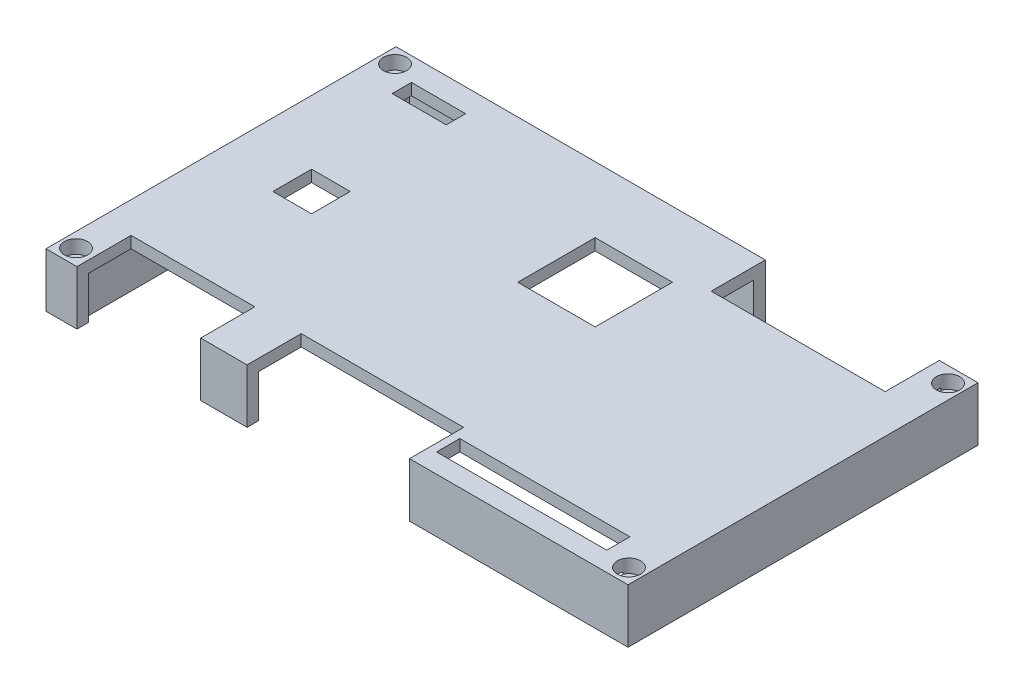
SolidWorks part; units mm, degrees
material "ABS"
ref_plane "Front Plane" through (0, 0, 0) normal (0, 0, 1) x (1, 0, 0)
ref_plane "Top Plane" through (0, 0, 0) normal (0, 1, 0) x (1, 0, 0)
ref_plane "Right Plane" through (0, 0, 0) normal (1, 0, 0) x (0, 0, -1)
other "Configuration Table"
sketch "Sketch1" plane through (0, 0, 0) normal (0, 1, 0) x (1, 0, 0)
  line L1 (75.25, -45.25) -> (-75.25, -45.25)
  line L2 (75.25, -45.25) -> (75.25, 45.25)
  line L3 (75.25, 45.25) -> (-75.25, 45.25)
  line L4 (-75.25, -45.25) -> (-75.25, 45.25)
  line L5 (75.25, -45.25) -> (-75.25, 45.25) construction
  line L6 (75.25, 45.25) -> (-75.25, -45.25) construction
  point P0 (0, 0)
  dimension "D1" = 90.5
  dimension "D2" = 150.5
extrude "Boss-Extrude1" add sketch "Sketch1" along normal blind 3
sketch "Sketch2" plane through (0, 0, 0) normal (0, -1, 0) x (-1, 0, 0)
  line L0 (75.25, -45.25) -> (-75.25, -45.25) construction
  line L1 (-68.75, 42.25) -> (68.75, 42.25)
  line L2 (-68.75, 42.25) -> (-68.75, -42.25)
  line L3 (-68.75, -42.25) -> (68.75, -42.25)
  line L4 (68.75, 42.25) -> (68.75, -42.25)
  line L5 (-68.75, 42.25) -> (68.75, -42.25) construction
  line L6 (-68.75, -42.25) -> (68.75, 42.25) construction
  line L7 (75.25, 45.25) -> (75.25, -45.25) construction
  line L8 (75.25, 45.25) -> (75.25, -45.25)
  line L9 (75.25, -45.25) -> (-75.25, -45.25)
  line L10 (-75.25, -45.25) -> (-75.25, 45.25)
  line L11 (-75.25, 45.25) -> (75.25, 45.25)
  point P0 (0, 0)
  dimension "D1" = 3
  dimension "D2" = 6.5
extrude "Boss-Extrude2" add sketch "Sketch2" along normal blind 11
sketch "Sketch3" plane through (0, 3, 0) normal (0, 1, 0) x (1, 0, 0)
  line L1 (71.5, -41.25) -> (-71.5, -41.25) construction
  line L2 (71.5, -41.25) -> (71.5, 41.25) construction
  line L3 (71.5, 41.25) -> (-71.5, 41.25) construction
  line L4 (-71.5, -41.25) -> (-71.5, 41.25) construction
  line L5 (71.5, -41.25) -> (-71.5, 41.25) construction
  line L6 (71.5, 41.25) -> (-71.5, -41.25) construction
  circle A0 centre (-71.5, 41.25) radius 1.5
  circle A1 centre (-71.5, -41.25) radius 1.5
  circle A2 centre (71.5, -41.25) radius 1.5
  circle A3 centre (71.5, 41.25) radius 1.5
  point P0 (0, 0)
  dimension "D3" = 3
  dimension "D4" = 3
  dimension "D5" = 3
  dimension "D6" = 3
  dimension "D1" = 82.5
  dimension "D2" = 143
extrude "Cut-Extrude1" cut sketch "Sketch3" against normal blind 31
sketch "Sketch4" plane through (0, 3, 0) normal (0, 1, 0) x (1, 0, 0)
  circle A0 centre (-71.5, 41.25) radius 3
  circle A1 centre (-71.5, -41.25) radius 3
  circle A2 centre (71.5, -41.25) radius 3
  circle A3 centre (71.5, 41.25) radius 3
  dimension "D1" = 6
  dimension "D2" = 6
  dimension "D3" = 6
  dimension "D4" = 6
extrude "Cut-Extrude2" cut sketch "Sketch4" against normal blind 3.5
sketch "Sketch5" plane through (0, 3, 0) normal (0, 1, 0) x (1, 0, 0)
  line L0 (-75.25, -45.25) -> (75.25, -45.25) construction
  line L1 (-67.25, -45.25) -> (-35.25, -45.25)
  line L2 (-67.25, -45.25) -> (-67.25, -31.25)
  line L3 (-67.25, -31.25) -> (-35.25, -31.25)
  line L4 (-35.25, -45.25) -> (-35.25, -31.25)
  line L5 (-75.25, 45.25) -> (-75.25, -45.25) construction
  line L6 (23.75, -37.25) -> (61.75, -37.25) construction
  line L7 (-23.25, -45.25) -> (18.75, -45.25)
  line L8 (-23.25, -45.25) -> (-23.25, -31.25)
  line L9 (-23.25, -31.25) -> (18.75, -31.25)
  line L10 (18.75, -45.25) -> (18.75, -31.25)
  line L11 (75.25, 45.25) -> (-75.25, 45.25) construction
  line L12 (64.75, -40.25) -> (20.75, -40.25)
  line L13 (64.75, -40.25) -> (64.75, -34.25)
  line L14 (64.75, -34.25) -> (20.75, -34.25)
  line L15 (20.75, -40.25) -> (20.75, -34.25)
  line L16 (64.75, -40.25) -> (20.75, -34.25) construction
  line L17 (64.75, -34.25) -> (20.75, -40.25) construction
  line L18 (65.25, 45.25) -> (20.25, 45.25)
  line L19 (65.25, 45.25) -> (65.25, 31.25)
  line L20 (65.25, 31.25) -> (20.25, 31.25)
  line L21 (20.25, 45.25) -> (20.25, 31.25)
  line L22 (75.25, -45.25) -> (75.25, 45.25) construction
  line L24 (-6.75, 28.25) -> (13.25, 28.25)
  line L25 (-6.75, 28.25) -> (-6.75, 8.25)
  line L26 (-6.75, 8.25) -> (13.25, 8.25)
  line L27 (13.25, 28.25) -> (13.25, 8.25)
  line L28 (-65.25, 39.25) -> (-51.25, 39.25)
  line L29 (-65.25, 39.25) -> (-65.25, 34.25)
  line L30 (-65.25, 34.25) -> (-51.25, 34.25)
  line L31 (-51.25, 39.25) -> (-51.25, 34.25)
  line L32 (-58.7443, 6.9122) -> (-48.7443, 6.9122)
  line L33 (-58.7443, 6.9122) -> (-58.7443, -3.0878)
  line L34 (-58.7443, -3.0878) -> (-48.7443, -3.0878)
  line L35 (-48.7443, 6.9122) -> (-48.7443, -3.0878)
  point P14 (42.75, -37.25)
  dimension "D1" = 8
  dimension "D2" = 14
  dimension "D3" = 32
  dimension "D4" = 12
  dimension "D5" = 42
  dimension "D6" = 38
  dimension "D7" = 8
  dimension "D8" = 5
  dimension "D9" = 6
  dimension "D10" = 44
  dimension "D11" = 10
  dimension "D12" = 14
  dimension "D13" = 45
  dimension "D14" = 82
  dimension "D15" = 20
  dimension "D16" = 20
  dimension "D17" = 17
  dimension "D18" = 10
  dimension "D19" = 14
  dimension "D20" = 5
  dimension "D21" = 6
  dimension "D22" = 10
extrude "Cut-Extrude3" cut sketch "Sketch5" against normal blind 15 contours L13 L12 L15 L14 | L19 L18 L21 L20 | L25 L24 L27 L26 | L8 L7 L10 L9 | L2 L1 L4 L3 | L33 L32 L35 L34 | L29 L28 L31 L30
sketch "Sketch7" plane through (-75.25, 0, 0) normal (-1, 0, 0) x (0, 0, 1)
  line L0 (45.25, -11) -> (-45.25, -11) construction
  line L1 (-34.1719, -11) -> (5.8281, -11)
  line L2 (-34.1719, -11) -> (-34.1719, -2)
  line L3 (-34.1719, -2) -> (5.8281, -2)
  line L4 (5.8281, -11) -> (5.8281, -2)
  dimension "D1" = 40
  dimension "D2" = 9
extrude "Cut-Extrude4" cut sketch "Sketch7" against normal blind 15
